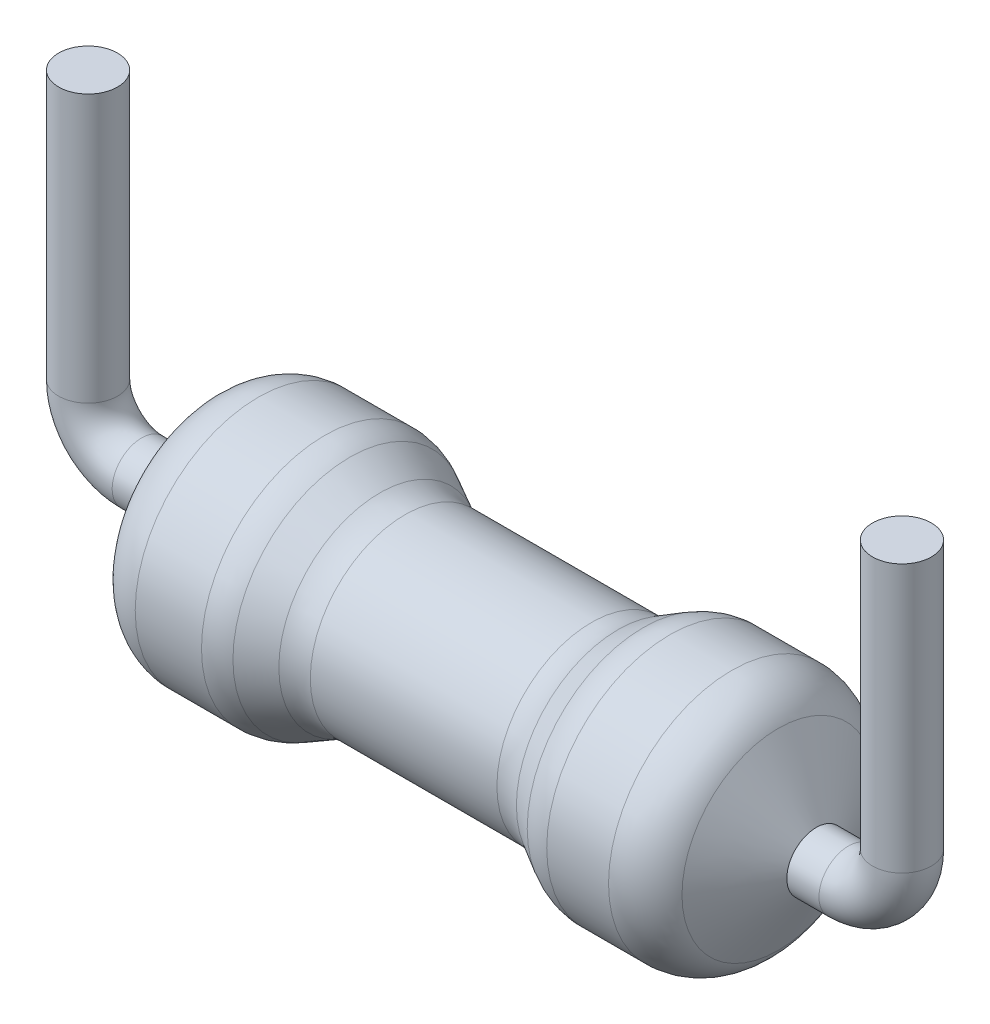
SolidWorks part; units mm, degrees
ref_plane "Front Plane" through (0, 0, 0) normal (0, 0, 1) x (1, 0, 0)
ref_plane "Top Plane" through (0, 0, 0) normal (0, 1, 0) x (1, 0, 0)
ref_plane "Right Plane" through (0, 0, 0) normal (1, 0, 0) x (0, 0, -1)
sketch "Sketch1" plane through (0, 0, 0) normal (0, 0, 1) x (1, 0, 0)
  line L0 (0, 0) -> (3, 0)
  line L1 (3, 0) -> (3, 0.275)
  line L2 (3, 0.275) -> (2.5, 1.15)
  line L3 (2.5, 1.15) -> (1.5, 1.15)
  line L4 (1.5, 1.15) -> (1.0338, 0.8836)
  line L5 (1.0338, 0.8836) -> (-0.9662, 0.8836)
  line L6 (-0.9662, 0.8836) -> (-1.4662, 1.15)
  line L7 (-1.4662, 1.15) -> (-2.5, 1.15)
  line L8 (-2.5, 1.15) -> (-3, 0.275)
  line L9 (-3, 0.275) -> (-3, 0)
  line L10 (-3, 0) -> (0, 0)
  point P2 (2, 1.15)
  dimension "D1" = 0.275
  dimension "D2" = 0.275
  dimension "D3" = 3
  dimension "D4" = 3
  dimension "D5" = 1.15
  dimension "D6" = 1.15
  dimension "D7" = 0.5
  dimension "D8" = 0.5
  dimension "D9" = 1
  dimension "D10" = 1.0338
  dimension "D11" = 2
  dimension "D12" = 0.5
  dimension "D13" = 0.8836
revolve "Revolve1" add sketch "Sketch1" angle 360 about L0
fillet "Fillet1" radius 0.5 6 edges at (-2.5, 0, 1.15) (-1.4662, 0, 1.15) (-0.9662, 0, 0.8836) (1.0338, 0, 0.8836) (1.5, 0, 1.15) (2.5, 0, 1.15)
sketch "Sketch4" plane through (3, 0, 0) normal (1, 0, 0) x (0, 0, -1)
  circle A0 centre (0, 0) radius 0.275
sketch "Sketch6" plane through (0, 0, 0) normal (0, 0, 1) x (1, 0, 0)
  line L0 (3, 0) -> (3.3, 0)
  line L1 (3.8, 0.5) -> (3.8, 3)
  line L2 (3, 0) -> (-3.3, 0)
  line L3 (-3.8, 0.5) -> (-3.8, 3)
  arc A0 (-3.3, 0) -> (-3.8, 0.5) centre (-3.3, 0.5) cw
  arc A1 (3.3, 0) -> (3.8, 0.5) centre (3.3, 0.5) ccw
  point P8 (-3.8, 0)
  point P11 (3.8, 0)
  dimension "D5" = 0.5
  dimension "D1" = 0.8
  dimension "D2" = 3
  dimension "D3" = 6.8
  dimension "D4" = 3
sweep "Sweep1" add profiles "Sketch4" path "Sketch6"
